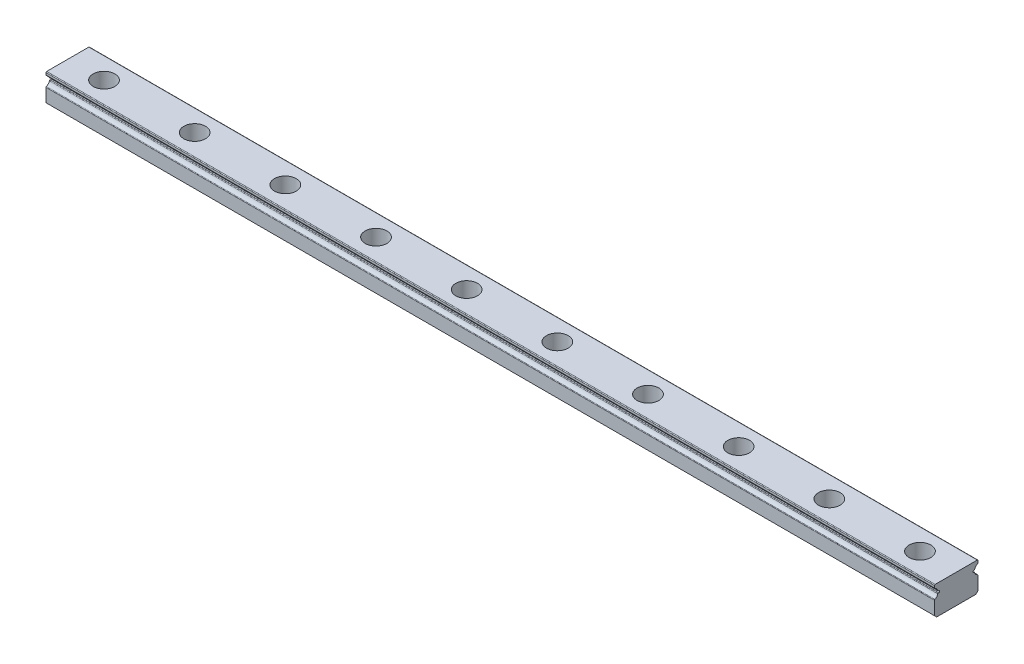
SolidWorks part; units mm, degrees
ref_plane "前视基准面" through (0, 0, 0) normal (0, 0, 1) x (1, 0, 0)
ref_plane "上视基准面" through (0, 0, 0) normal (0, 1, 0) x (1, 0, 0)
ref_plane "右视基准面" through (0, 0, 0) normal (1, 0, 0) x (0, 0, -1)
other "Configuration Table"
ref_plane "基准面1" through (0, 4, 0) normal (0, 1, 0) x (1, 0, 0)
sketch "草图1" plane through (0, 4, 0) normal (0, 1, 0) x (1, 0, 0)
  line L0 (122.5, -6) -> (122.5, 6)
  line L1 (122.5, 6) -> (-122.5, 6)
  line L2 (-122.5, 6) -> (-122.5, -6)
  line L3 (-122.5, -6) -> (122.5, -6)
extrude "凸台-拉伸1" add sketch "草图1" against normal blind 8
sketch "草图2" plane through (122.5, 0, 0) normal (1, 0, 0) x (0, 0, -1)
  line L0 (6, 1.51) -> (6, 2.01)
  line L1 (6, 2.01) -> (4.8, 2.01)
  line L2 (4.8, 1.51) -> (6, 1.51)
  arc A0 (4.8, 2.01) -> (4.8, 1.51) centre (4.8, 1.76) ccw
extrude "切除-拉伸1" cut sketch "草图2" against normal through all
sketch "草图3" plane through (122.5, 0, 0) normal (1, 0, 0) x (0, 0, -1)
  line L0 (6, 2.01) -> (6, 3.1111)
  line L1 (5.04, 2.01) -> (6, 2.01)
  arc A0 (6, 3.1111) -> (5.04, 2.01) centre (6.4382, 1.76) ccw
extrude "切除-拉伸2" cut sketch "草图3" against normal through all
sketch "草图4" plane through (122.5, 0, 0) normal (1, 0, 0) x (0, 0, -1)
  line L0 (6, 1.51) -> (5.04, 1.51)
  line L1 (6, 0.4089) -> (6, 1.51)
  arc A0 (5.04, 1.51) -> (6, 0.4089) centre (6.4382, 1.76) ccw
extrude "切除-拉伸3" cut sketch "草图4" against normal through all
sketch "草图5" plane through (122.5, 0, 0) normal (1, 0, 0) x (0, 0, -1)
  line L0 (-6, 2.01) -> (-6, 1.51)
  line L1 (-6, 1.51) -> (-4.8, 1.51)
  line L2 (-4.8, 2.01) -> (-6, 2.01)
  arc A0 (-4.8, 1.51) -> (-4.8, 2.01) centre (-4.8, 1.76) ccw
extrude "切除-拉伸4" cut sketch "草图5" against normal through all
sketch "草图6" plane through (122.5, 0, 0) normal (1, 0, 0) x (0, 0, -1)
  line L0 (-6, 1.51) -> (-6, 0.4089)
  line L1 (-5.04, 1.51) -> (-6, 1.51)
  arc A0 (-6, 0.4089) -> (-5.04, 1.51) centre (-6.4382, 1.76) ccw
extrude "切除-拉伸5" cut sketch "草图6" against normal through all
sketch "草图7" plane through (122.5, 0, 0) normal (1, 0, 0) x (0, 0, -1)
  line L0 (-6, 2.01) -> (-5.04, 2.01)
  line L1 (-6, 3.1111) -> (-6, 2.01)
  arc A0 (-5.04, 2.01) -> (-6, 3.1111) centre (-6.4382, 1.76) ccw
extrude "切除-拉伸6" cut sketch "草图7" against normal through all
hole_wizard "M3 六角头机械螺钉的柱形沉头孔1" positions "草图9" profile "草图8" counterbore size "M3" standard "ANSI Metric"
sketch "草图9" plane through (0, 4, 0) normal (0, 1, 0) x (1, 0, 0)
  point P0 (-112.5, 0)
  point P1 (-87.5, 0)
  point P2 (-62.5, 0)
  point P3 (-37.5, 0)
  point P4 (-12.5, 0)
  point P5 (12.5, 0)
  point P6 (37.5, 0)
  point P7 (62.5, 0)
  point P8 (87.5, 0)
  point P9 (112.5, 0)
sketch "草图8" plane through (-112.5, 4, 0) normal (1, 0, 0) x (0, 0, 1)
  line L0 (0, 0) -> (0, 8)
  line L1 (0, 8) -> (1.75, 8)
  line L3 (1.75, 8) -> (1.75, 4.5)
  line L4 (1.75, 4.5) -> (2.9999, 4.5)
  line L5 (2.9999, 4.5) -> (2.9999, 0)
  line L7 (2.9999, 0) -> (0, 0)
  line L11 (0, -6.35) -> (0, 107.95) construction
  dimension "通孔孔直径" = 3.5
  dimension "通孔孔深度" = 8
  dimension "柱形沉头孔直径" = 5.9999
  dimension "柱形沉头孔深度" = 4.5
chamfer "倒角1" distance 0.6 angle 45 2 edges at (0, -4, -6) (0, -4, 6)
fillet "圆角1" radius 0.2 10 edges at (0, 3.1111, -6) (0, 1.51, -5.04) (0, 4, -6) (0, 1.51, 5.04) (0, 2.01, -5.04) (0, 2.01, 5.04) (0, 4, 6) (0, 3.1111, 6) (0, 0.4089, -6) (0, 0.4089, 6)
